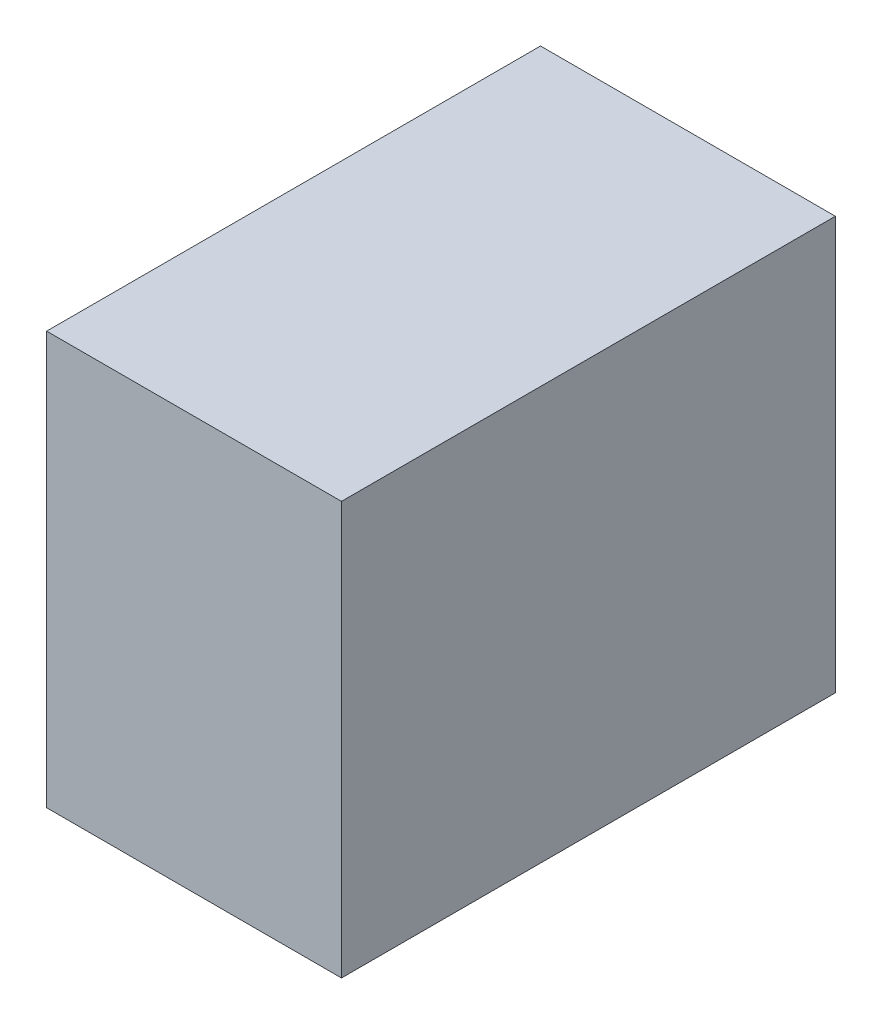
SolidWorks part; units mm, degrees
material "自定义塑料"
ref_plane "前视基准面" through (0, 0, 0) normal (0, 0, 1) x (1, 0, 0)
ref_plane "上视基准面" through (0, 0, 0) normal (0, 1, 0) x (1, 0, 0)
ref_plane "右视基准面" through (0, 0, 0) normal (1, 0, 0) x (0, 0, -1)
sketch "草图1" plane through (0, 0, 0) normal (0, 0, 1) x (1, 0, 0)
  line L1 (-24.6154, 22.8718) -> (15.3846, 22.8718)
  line L2 (-24.6154, 22.8718) -> (-24.6154, -33.1282)
  line L3 (-24.6154, -33.1282) -> (15.3846, -33.1282)
  line L4 (15.3846, 22.8718) -> (15.3846, -33.1282)
  dimension "D1" = 56
  dimension "D2" = 40
extrude "凸台-拉伸1" add sketch "草图1" along normal blind 67
